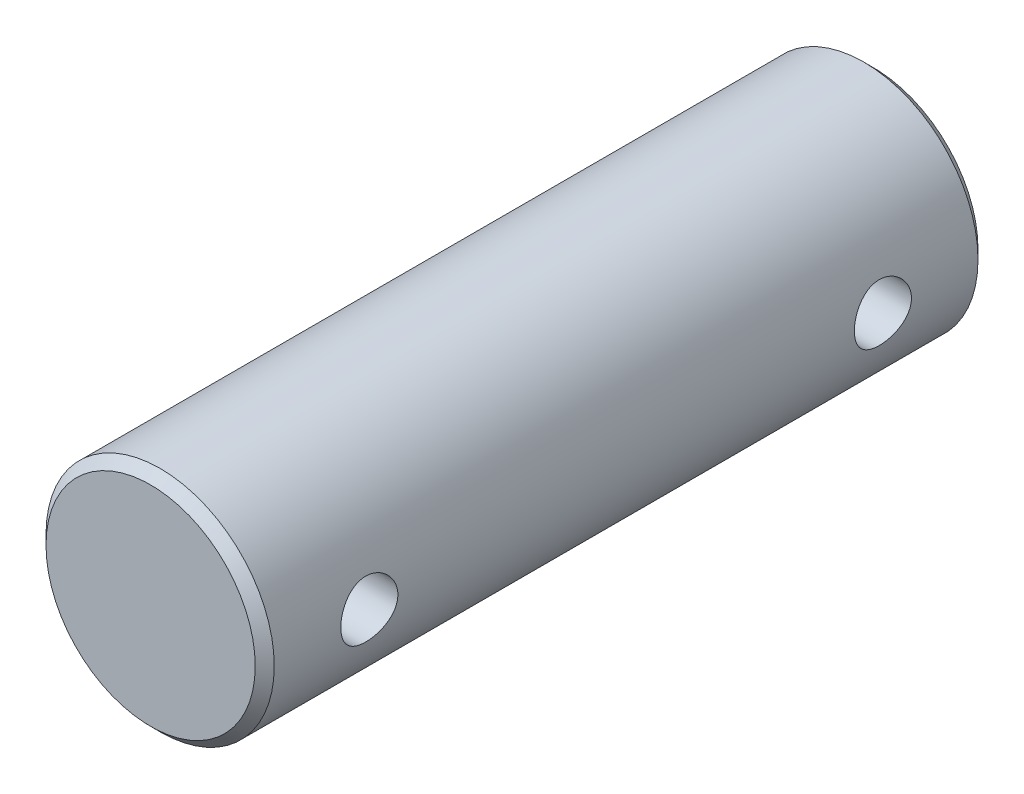
SolidWorks part; units mm, degrees
ref_plane "Front Plane" through (0, 0, 0) normal (0, 0, 1) x (1, 0, 0)
ref_plane "Top Plane" through (0, 0, 0) normal (0, 1, 0) x (1, 0, 0)
ref_plane "Right Plane" through (0, 0, 0) normal (1, 0, 0) x (0, 0, -1)
sketch "Sketch1" plane through (0, 0, 0) normal (0, 0, 1) x (1, 0, 0)
  circle A0 centre (0, 0) radius 6
  dimension "D1" = 12
extrude "Boss-Extrude1" add sketch "Sketch1" along normal mid plane 38
chamfer "Chamfer1" distance 0.5 angle 45 2 edges at (6, 0, -19) (6, 0, 19)
sketch "Sketch2" plane through (0, 0, 0) normal (1, 0, 0) x (0, 0, -1)
  line L0 (-18.5, -6) -> (-18.5, 6) construction
  line L1 (18.5, 6) -> (18.5, -6) construction
  circle A0 centre (13.5, 0) radius 1.5
  circle A1 centre (-13.5, 0) radius 1.5
  dimension "D1" = 3
  dimension "D4" = 3
  dimension "D2" = 5
  dimension "D3" = 5
extrude "Cut-Extrude1" cut sketch "Sketch2" against normal mid plane 38 contours A1 | A0
